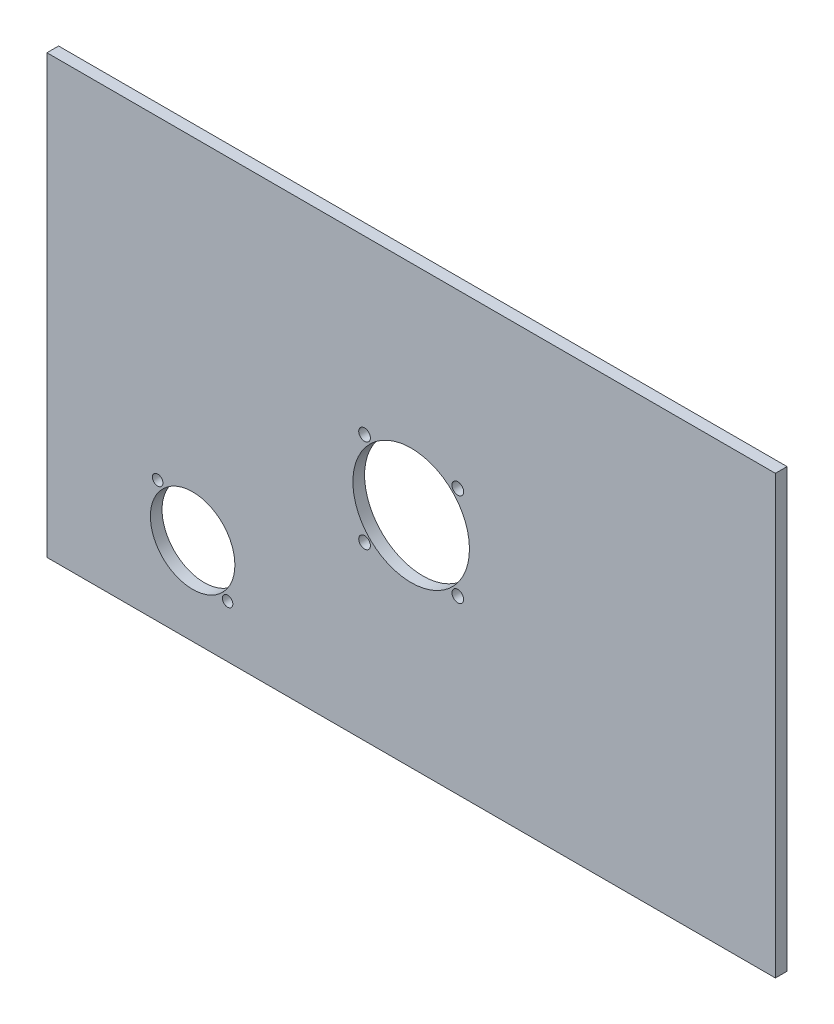
SolidWorks part; units mm, degrees
ref_plane "Front Plane" through (0, 0, 0) normal (0, 0, 1) x (1, 0, 0)
ref_plane "Top Plane" through (0, 0, 0) normal (0, 1, 0) x (1, 0, 0)
ref_plane "Right Plane" through (0, 0, 0) normal (1, 0, 0) x (0, 0, -1)
sketch "Sketch1" plane through (0, 0, 0) normal (0, 0, 1) x (1, 0, 0)
  line L1 (-112.8247, 64.3669) -> (137.1753, 64.3669)
  line L2 (-112.8247, 64.3669) -> (-112.8247, -85.6331)
  line L3 (-112.8247, -85.6331) -> (137.1753, -85.6331)
  line L4 (137.1753, 64.3669) -> (137.1753, -85.6331)
  dimension "D1" = 250
  dimension "D2" = 150
extrude "Boss-Extrude1" add sketch "Sketch1" along normal blind 4
sketch "Sketch2" plane through (0, 0, 4) normal (0, 0, 1) x (1, 0, 0)
  circle A0 centre (12.1753, -10.6331) radius 20
extrude "Cut-Extrude1" cut sketch "Sketch2" against normal blind 4 contours A0
sketch "Sketch3" plane through (0, 0, 4) normal (0, 0, 1) x (1, 0, 0)
  circle A0 centre (-3.8247, 5.3669) radius 2
  circle A2 centre (28.1753, 5.3669) radius 2
  circle A3 centre (28.1753, -26.6331) radius 2
  circle A4 centre (-3.8247, -26.6331) radius 2
  point P25 (12.1753, -10.6331)
  dimension "D1" = 32
  dimension "D3" = 4
  dimension "D4" = 4
  dimension "D2" = 32
extrude "Cut-Extrude2" cut sketch "Sketch3" against normal blind 4
sketch "Sketch4" plane through (0, 0, 4) normal (0, 0, 1) x (1, 0, 0)
  line L2 (-112.8247, -85.6331) -> (137.1753, -85.6331) construction
  line L4 (-112.8247, 64.3669) -> (-112.8247, -85.6331) construction
  circle A0 centre (-62.8247, -55.6331) radius 14.5
  circle A1 centre (-74.8247, -43.6331) radius 1.8
  circle A2 centre (-50.8247, -67.6331) radius 1.8
  dimension "D1" = 12
  dimension "D2" = 12
  dimension "D3" = 30
  dimension "D4" = 50
  dimension "D5" = 12
  dimension "D6" = 12
extrude "Cut-Extrude4" cut sketch "Sketch4" against normal blind 4
